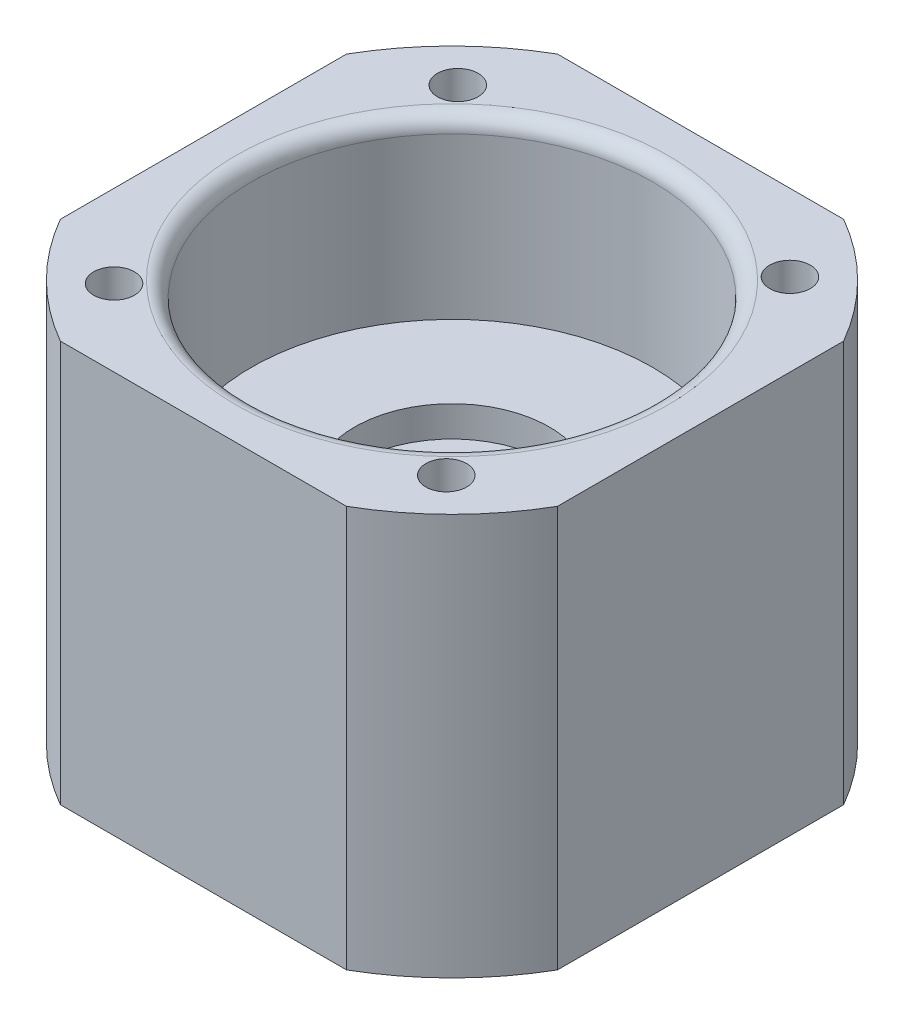
SolidWorks part; units mm, degrees
ref_plane "Front Plane" through (0, 0, 0) normal (0, 0, 1) x (1, 0, 0)
ref_plane "Top Plane" through (0, 0, 0) normal (0, 1, 0) x (1, 0, 0)
ref_plane "Right Plane" through (0, 0, 0) normal (1, 0, 0) x (0, 0, -1)
sketch "Body Profile" plane through (0, 0, 0) normal (0, 0, 1) x (1, 0, 0)
  line L0 (-38.1, 25.4) -> (-31.75, 25.4)
  line L1 (-31.75, 25.4) -> (-31.75, 3.302)
  line L2 (-31.75, 3.302) -> (-25.4, 3.302)
  line L3 (-25.4, 3.302) -> (-25.4, 0)
  line L4 (-38.1, 0) -> (-38.1, 25.4)
  line L5 (-38.1, 0) -> (-25.4, 0)
  line L7 (0, 0) -> (0, -13.8986) construction
  line L8 (0, -13.8986) -> (0, 36.21) construction
  dimension "D1" = 6.35
  dimension "D2" = 25.4
  dimension "D3" = 12.7
  dimension "D4" = 3.302
  dimension "D5" = 25.4
revolve "Revolve1" [suppressed] add sketch "Body Profile" angle 360 about L8
sketch "Vent Valve Body Profile" plane through (0, 0, 0) normal (0, 0, 1) x (1, 0, 0)
  line L0 (-19.05, 26.67) -> (-19.05, 0)
  line L1 (-19.05, 0) -> (-4.445, 0)
  line L2 (-4.445, 0) -> (-4.445, 3.302)
  line L3 (-4.445, 3.302) -> (-2.794, 3.302)
  line L4 (-2.794, 3.302) -> (-2.794, 12.954)
  line L5 (-2.794, 12.954) -> (-6.477, 12.954)
  line L6 (-6.477, 12.954) -> (-6.477, 14.986)
  line L7 (-6.477, 14.986) -> (-13.335, 14.986)
  line L8 (-13.335, 14.986) -> (-13.335, 26.67)
  line L9 (-13.335, 26.67) -> (-19.05, 26.67)
  line L10 (0, 11.1358) -> (0, -4.0909) construction
  dimension "D1" = 5.588
  dimension "D2" = 26.67
  dimension "D3" = 11.684
  dimension "D4" = 26.67
  dimension "D5" = 13.716
  dimension "D6" = 8.89
  dimension "D7" = 12.954
  dimension "D8" = 38.1
  dimension "D9" = 23.368
revolve "Revolve2" add sketch "Vent Valve Body Profile" angle 360 about L10
sketch "Sketch4" plane through (0, 26.67, 0) normal (0, 1, 0) x (1, 0, 0)
  line L1 (-16.51, -16.51) -> (16.51, -16.51)
  line L2 (-16.51, -16.51) -> (-16.51, 16.51)
  line L3 (-16.51, 16.51) -> (16.51, 16.51)
  line L4 (16.51, -16.51) -> (16.51, 16.51)
  line L5 (-16.51, -16.51) -> (16.51, 16.51) construction
  line L6 (-16.51, 16.51) -> (16.51, -16.51) construction
  point P1 (0, 0)
  dimension "D1" = 33.02
extrude "Cut-Extrude2" cut sketch "Sketch4" against normal through all both and the other way through all flip side to cut
hole_wizard "#6-32 Tapped Hole2" positions "Sketch7" profile "Sketch8" tap size "#6-32" standard "ANSI Inch"
sketch "Sketch7" plane through (0, 26.67, 0) normal (0, 1, 0) x (1, 0, 0)
  circle A0 centre (0, 0) radius 15.875
  point P0 (11.0326, 11.4148)
  point P2 (11.0326, -11.4148)
  point P4 (-11.0326, -11.4148)
  point P6 (-11.0326, 11.4148)
  dimension "D1" = 31.75
sketch "Sketch8" plane through (11.0326, 26.67, -11.4148) normal (1, 0, 0) x (0, 0, 1)
  line L0 (0, 0) -> (0, 10.2107)
  line L1 (0, 10.2107) -> (1.3525, 9.398)
  line L2 (1.3525, 9.398) -> (1.3525, 0)
  line L5 (1.3525, 0) -> (0, 0)
  line L10 (0, 10.2107) -> (-1.3525, 9.398) construction
  line L11 (0, -6.35) -> (0, 107.95) construction
  dimension "Tap Drill Dia." = 2.7051
  dimension "Tap Drill Depth" = 9.398
  dimension "Drill Angle" = 118
cosmetic thread "Hole Thread5" parameters "D1"=7.112, "D2"=3.5052
cosmetic thread "Hole Thread6" parameters "D1"=7.112, "D2"=3.5052
cosmetic thread "Hole Thread9" parameters "D1"=7.112, "D2"=3.5052
cosmetic thread "Hole Thread10" parameters "D1"=7.112, "D2"=3.5052
fillet "Fillet1" radius 1.016 1 edges at (0, 26.67, 13.335)
